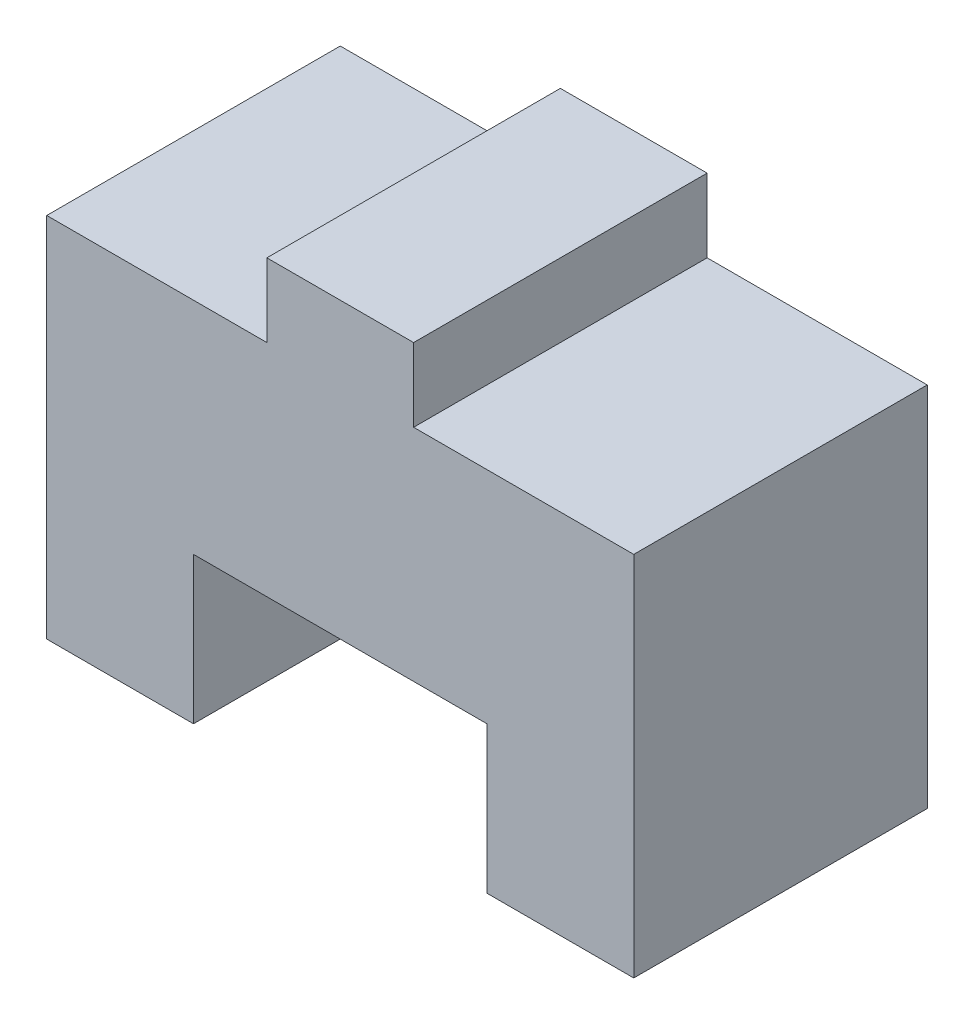
SolidWorks part; units mm, degrees
ref_plane "Front Plane" through (0, 0, 0) normal (0, 0, 1) x (1, 0, 0)
ref_plane "Top Plane" through (0, 0, 0) normal (0, 1, 0) x (1, 0, 0)
ref_plane "Right Plane" through (0, 0, 0) normal (1, 0, 0) x (0, 0, -1)
sketch "Sketch1" plane through (0, 0, 0) normal (0, 0, 1) x (1, 0, 0)
  line L0 (0, 0) -> (10, 0)
  line L1 (10, 0) -> (10, 10)
  line L2 (10, 10) -> (30, 10)
  line L3 (30, 10) -> (30, 0)
  line L4 (30, 0) -> (40, 0)
  line L5 (40, 0) -> (40, 25)
  line L6 (40, 25) -> (25, 25)
  line L7 (25, 25) -> (25, 30)
  line L8 (25, 30) -> (15, 30)
  line L9 (15, 30) -> (15, 25)
  line L10 (15, 25) -> (0, 25)
  line L11 (0, 25) -> (0, 0)
  dimension "D1" = 10
  dimension "D2" = 15
  dimension "D3" = 5
  dimension "D4" = 25
  dimension "D5" = 40
extrude "Boss-Extrude1" add sketch "Sketch1" along normal blind 20
